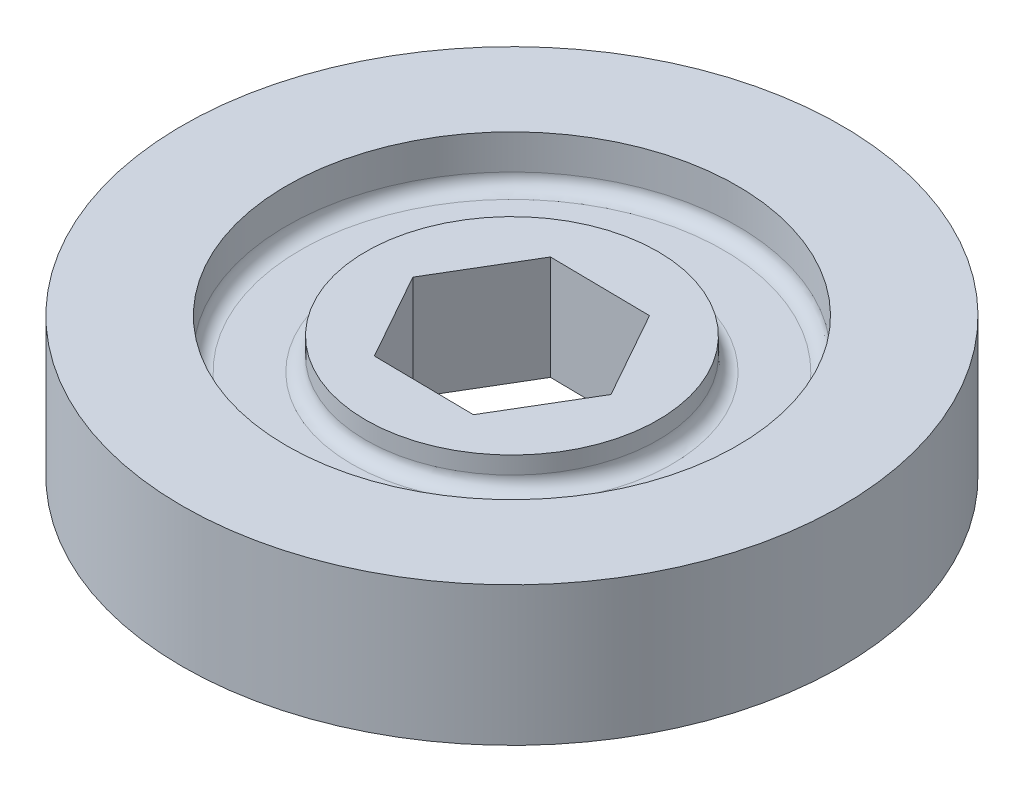
SolidWorks part; units mm, degrees
ref_plane "Front Plane" through (0, 0, 0) normal (0, 0, 1) x (1, 0, 0)
ref_plane "Top Plane" through (0, 0, 0) normal (0, 1, 0) x (1, 0, 0)
ref_plane "Right Plane" through (0, 0, 0) normal (1, 0, 0) x (0, 0, -1)
sketch "Sketch1" plane through (0, 0, 0) normal (0, 1, 0) x (1, 0, 0)
  circle A0 centre (0, 0) radius 23.7
  dimension "D1" = 47.4
extrude "Boss-Extrude1" add sketch "Sketch1" along normal blind 10
sketch "Sketch2" plane through (0, 10, 0) normal (0, 1, 0) x (1, 0, 0)
  circle A0 centre (0, 0) radius 16.2
  circle A1 centre (0, 0) radius 23.7 construction
  dimension "D1" = 7.5
extrude "Cut-Extrude1" cut sketch "Sketch2" against normal blind 3.5
sketch "Sketch3" plane through (0, 0, 0) normal (0, -1, 0) x (1, 0, 0)
  circle A0 centre (0, 0) radius 16.2
  circle A1 centre (0, 0) radius 23.7 construction
  dimension "D1" = 7.5
extrude "Cut-Extrude2" cut sketch "Sketch3" against normal blind 3.5
sketch "Sketch5" plane through (0, 6.5, 0) normal (0, 1, 0) x (1, 0, 0)
  circle A0 centre (0, 0) radius 10.5
  dimension "D1" = 21
extrude "Boss-Extrude2" add sketch "Sketch5" along normal blind 2.25
sketch "Sketch6" plane through (0, 3.5, 0) normal (0, -1, 0) x (1, 0, 0)
  circle A0 centre (0, 0) radius 10.5
  dimension "D1" = 21
extrude "Boss-Extrude3" add sketch "Sketch6" along normal blind 2.25
sketch "Sketch4" plane through (0, 6.5, 0) normal (0, 1, 0) x (1, 0, 0)
  line L1 (3.6896, 6.2024) -> (-3.5266, 6.2965)
  line L2 (-3.5266, 6.2965) -> (-7.2163, 0.0941)
  line L3 (-7.2163, 0.0941) -> (-3.6896, -6.2024)
  line L4 (-3.6896, -6.2024) -> (3.5266, -6.2965)
  line L5 (3.5266, -6.2965) -> (7.2163, -0.0941)
  line L6 (7.2163, -0.0941) -> (3.6896, 6.2024)
  circle A0 centre (0, 0) radius 6.25 construction
  dimension "D1" = 12.5
extrude "Cut-Extrude3" cut sketch "Sketch4" against normal through all both and the other way through all
fillet "Fillet1" radius 1 2 edges at (0, 3.5, -16.2) (0, 6.5, 16.2)
fillet "Fillet2" radius 1 2 edges at (0, 3.5, -10.5) (0, 6.5, 10.5)
